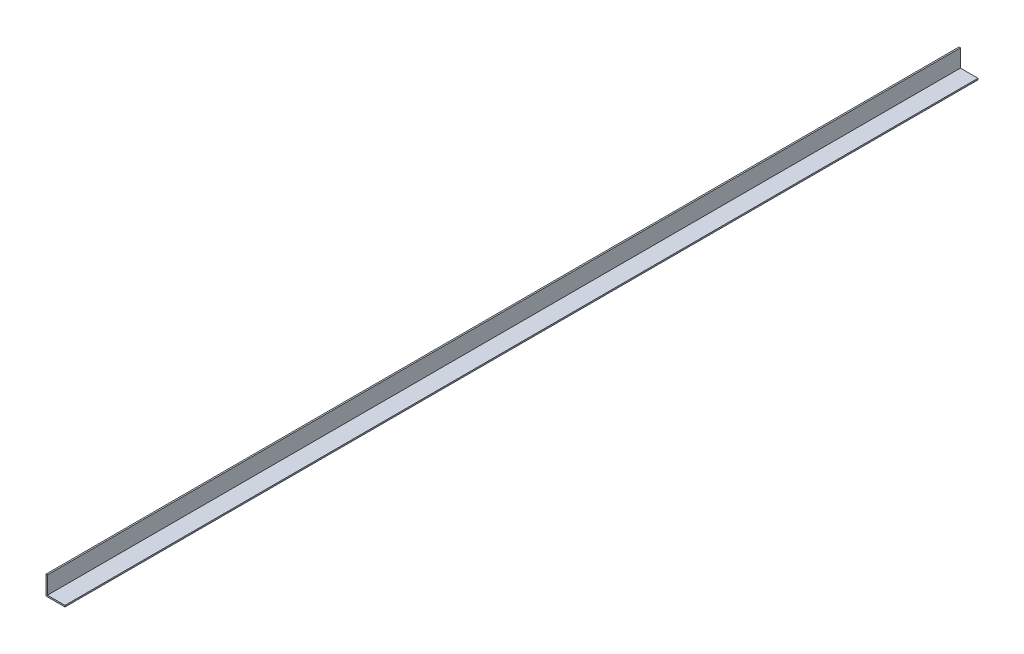
SolidWorks part; units mm, degrees
material "ASTM A36 Acero"
ref_plane "Alzado" through (0, 0, 0) normal (0, 0, 1) x (1, 0, 0)
ref_plane "Planta" through (0, 0, 0) normal (0, 1, 0) x (1, 0, 0)
ref_plane "Vista lateral" through (0, 0, 0) normal (1, 0, 0) x (0, 0, -1)
sketch "Croquis1" plane through (0, 0, 0) normal (0, 0, 1) x (1, 0, 0)
  line L0 (0, 127) -> (0, 0)
  line L1 (0, 0) -> (127, 0)
  line L2 (127, 0) -> (127, 9.53)
  line L3 (127, 9.53) -> (9.53, 9.53)
  line L4 (9.53, 9.53) -> (9.53, 127)
  line L5 (9.53, 127) -> (0, 127)
  dimension "D1" = 9.53
  dimension "D2" = 127
extrude "Saliente-Extruir1" add sketch "Croquis1" against normal blind 6100
